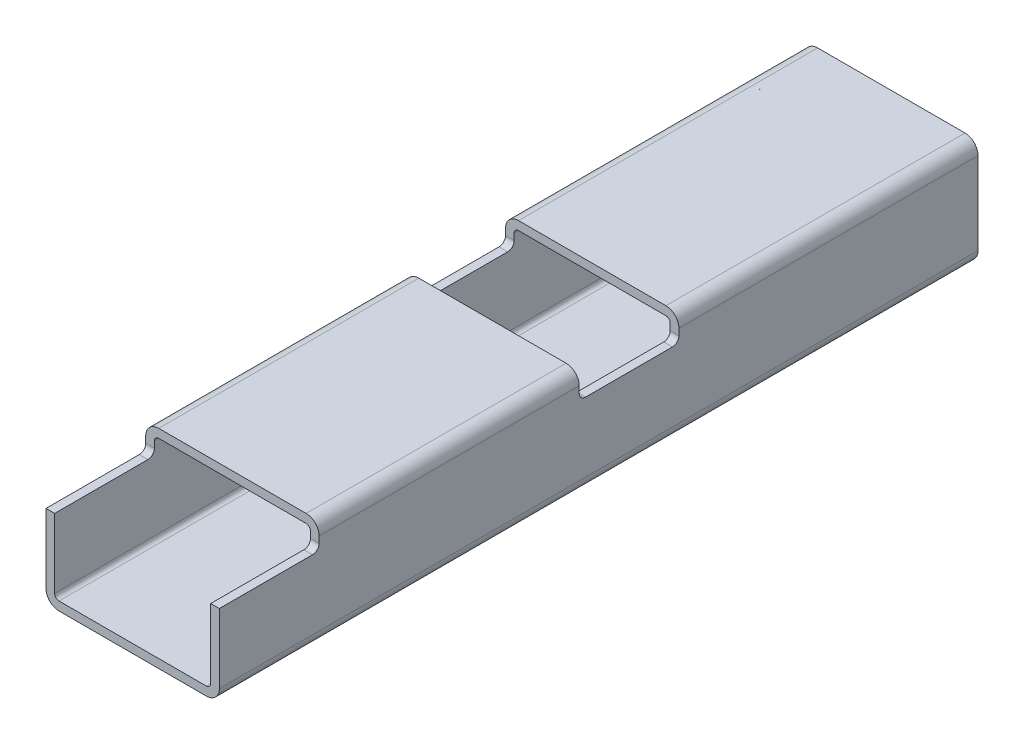
SolidWorks part; units mm, degrees
material "Простая углеродистая сталь"
ref_plane "Front" through (0, 0, 0) normal (0, 0, 1) x (1, 0, 0)
ref_plane "Top" through (0, 0, 0) normal (0, 1, 0) x (1, 0, 0)
ref_plane "Right" through (0, 0, 0) normal (1, 0, 0) x (0, 0, -1)
sketch "Эскиз1" plane through (0, 0, 0) normal (0, 0, 1) x (1, 0, 0)
  line L0 (-34, -21) -> (34, -21)
  line L1 (-34, -25) -> (34, -25)
  line L2 (-40, -19) -> (-40, 19)
  line L3 (-34, 25) -> (34, 25)
  line L4 (40, -19) -> (40, 19)
  line L5 (-40, -25) -> (40, 25) construction
  line L6 (-40, 25) -> (40, -25) construction
  line L7 (36, -19) -> (36, 19)
  line L8 (-34, 21) -> (34, 21)
  line L9 (-36, -19) -> (-36, 19)
  arc A0 (-34, -25) -> (-40, -19) centre (-34, -19) cw
  arc A1 (34, -25) -> (40, -19) centre (34, -19) ccw
  arc A2 (34, 25) -> (40, 19) centre (34, 19) cw
  arc A3 (-40, 19) -> (-34, 25) centre (-34, 19) cw
  arc A4 (34, -21) -> (36, -19) centre (34, -19) ccw
  arc A5 (34, 21) -> (36, 19) centre (34, 19) cw
  arc A6 (-36, 19) -> (-34, 21) centre (-34, 19) cw
  arc A7 (-34, -21) -> (-36, -19) centre (-34, -19) cw
  point P0 (0, 0)
  dimension "D3" = 6
  dimension "D1" = 80
  dimension "D2" = 50
  dimension "D4" = 4
extrude "Бобышка-Вытянуть1" add sketch "Эскиз1" along normal blind 350
sketch "Эскиз2" plane through (40, 0, 0) normal (1, 0, 0) x (0, 0, -1)
  line L0 (-350, -19) -> (-350, 19) construction
  line L1 (-350, 13) -> (-307, 13)
  line L2 (-350, 13) -> (-350, 25)
  line L3 (-350, 25) -> (-304, 25)
  line L4 (-304, 16) -> (-304, 25)
  line L5 (-350, 25) -> (0, 25) construction
  line L6 (-181, 13) -> (-141, 13)
  line L7 (-184, 16) -> (-184, 25)
  line L8 (-184, 25) -> (-138, 25)
  line L9 (-138, 16) -> (-138, 25)
  arc A0 (-181, 13) -> (-184, 16) centre (-181, 16) cw
  arc A1 (-307, 13) -> (-304, 16) centre (-307, 16) ccw
  arc A2 (-141, 13) -> (-138, 16) centre (-141, 16) ccw
  dimension "D4" = 3
  dimension "D1" = 46
  dimension "D2" = 120
  dimension "D3" = 12
extrude "Вырез-Вытянуть1" cut sketch "Эскиз2" against normal through all
